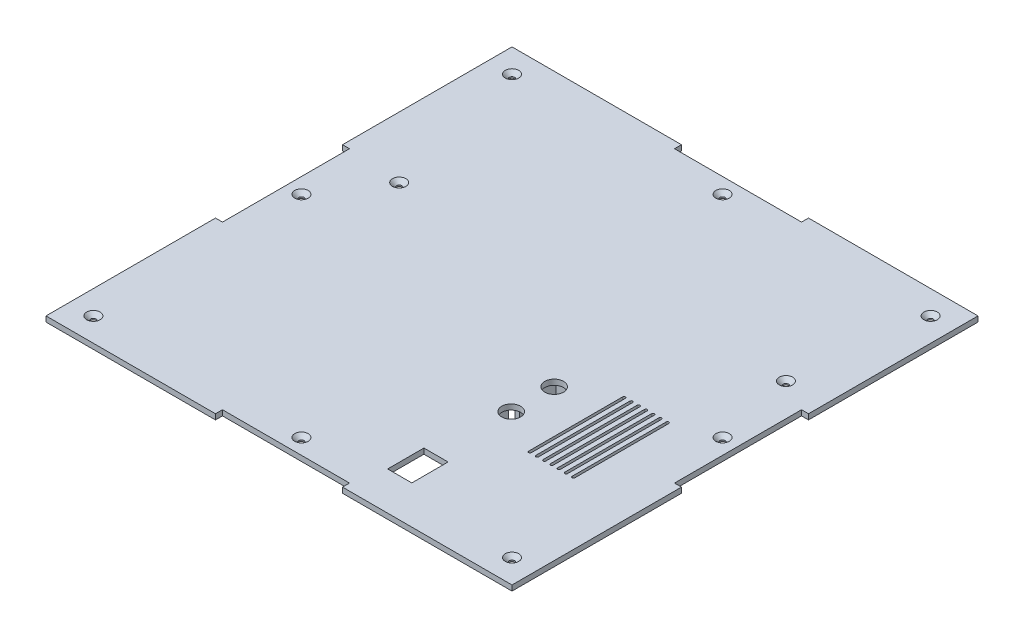
SolidWorks part; units mm, degrees
ref_plane "Front Plane" through (0, 0, 0) normal (0, 0, 1) x (1, 0, 0)
ref_plane "Top Plane" through (0, 0, 0) normal (0, 1, 0) x (1, 0, 0)
ref_plane "Right Plane" through (0, 0, 0) normal (1, 0, 0) x (0, 0, -1)
sketch "Sketch1" plane through (0, 0, 0) normal (0, 1, 0) x (1, 0, 0)
  line L0 (23.4, -87) -> (87, -87) construction
  line L1 (23.4, -84.4) -> (23.4, -87) construction
  line L2 (-23.4, -84.4) -> (23.4, -84.4) construction
  line L3 (-23.4, -87) -> (-23.4, -84.4) construction
  line L4 (-87, -87) -> (-23.4, -87) construction
  line L5 (-87, -23.4) -> (-87, -87) construction
  line L6 (-84.4, -23.4) -> (-87, -23.4) construction
  line L7 (-84.4, 23.4) -> (-84.4, -23.4) construction
  line L8 (-87, 23.4) -> (-84.4, 23.4) construction
  line L9 (-87, 87) -> (-87, 23.4) construction
  line L10 (-23.4, 87) -> (-87, 87) construction
  line L11 (-23.4, 84.4) -> (-23.4, 87) construction
  line L12 (23.4, 84.4) -> (-23.4, 84.4) construction
  line L13 (23.4, 87) -> (23.4, 84.4) construction
  line L14 (87, 87) -> (23.4, 87) construction
  line L15 (87, 23.4) -> (87, 87) construction
  line L16 (84.4, 23.4) -> (87, 23.4) construction
  line L17 (84.4, -23.4) -> (84.4, 23.4) construction
  line L18 (87, -23.4) -> (84.4, -23.4) construction
  line L19 (87, -87) -> (87, -23.4) construction
  line L20 (23.65, -86.75) -> (86.75, -86.75)
  line L21 (86.75, -86.75) -> (86.75, -23.65)
  line L22 (86.75, -23.65) -> (84.15, -23.65)
  line L23 (84.15, -23.65) -> (84.15, 23.65)
  line L24 (84.15, 23.65) -> (86.75, 23.65)
  line L25 (86.75, 23.65) -> (86.75, 86.75)
  line L26 (86.75, 86.75) -> (23.65, 86.75)
  line L27 (23.65, 86.75) -> (23.65, 84.15)
  line L28 (23.65, 84.15) -> (-23.65, 84.15)
  line L29 (-23.65, 84.15) -> (-23.65, 86.75)
  line L30 (-23.65, 86.75) -> (-86.75, 86.75)
  line L31 (-86.75, 86.75) -> (-86.75, 23.65)
  line L32 (-86.75, 23.65) -> (-84.15, 23.65)
  line L33 (-84.15, 23.65) -> (-84.15, -23.65)
  line L34 (-84.15, -23.65) -> (-86.75, -23.65)
  line L35 (-86.75, -23.65) -> (-86.75, -86.75)
  line L36 (-86.75, -86.75) -> (-23.65, -86.75)
  line L37 (-23.65, -86.75) -> (-23.65, -84.15)
  line L38 (-23.65, -84.15) -> (23.65, -84.15)
  line L39 (23.65, -84.15) -> (23.65, -86.75)
  point P20 (0, 84.4)
  point P22 (84.4, 0)
  dimension "D1" = 174
  dimension "D2" = 63.6
  dimension "D3" = 46.8
  dimension "D4" = 174
  dimension "D5" = 63.6
  dimension "D6" = 46.8
  dimension "D7" = 46.8
  dimension "D8" = 63.6
  dimension "D9" = 63.6
  dimension "D10" = 46.8
  dimension "D11" = 2.6
  dimension "D12" = 2.6
  dimension "D13" = 2.6
  dimension "D14" = 2.6
  dimension "D15" = 0.25
extrude "Boss-Extrude1" add sketch "Sketch1" along normal blind 2
sketch "Sketch2" plane through (0, 0, 0) normal (0, -1, 0) x (1, 0, 0)
  circle A0 centre (-77.9289, 77.9289) radius 1
  circle A1 centre (0, 78.4) radius 1
  circle A2 centre (77.9289, 77.9289) radius 1
  circle A3 centre (-78.4, 0) radius 1
  circle A4 centre (78.4, 0) radius 1
  circle A5 centre (72, -30) radius 1
  circle A6 centre (-64, -22) radius 1
  circle A7 centre (-77.9289, -77.9289) radius 1
  circle A8 centre (0, -78.4) radius 1
  circle A9 centre (77.9289, -77.9289) radius 1
  dimension "D1" = 2
  dimension "D2" = 2
  dimension "D3" = 2
  dimension "D4" = 2
  dimension "D5" = 2
  dimension "D6" = 2
  dimension "D7" = 2
  dimension "D8" = 2
  dimension "D9" = 2
  dimension "D10" = 2
extrude "Cut-Extrude1" cut sketch "Sketch2" against normal through all
chamfer "Chamfer1" distance 1.5 angle 45 10 edges at (-77.9289, 2, -78.9289) (0, 2, -79.4) (77.9289, 2, -78.9289) (72, 2, -31) (78.4, 2, -1) (-64, 2, -23) (-78.4, 2, -1) (-77.9289, 2, 76.9289) (0, 2, 77.4) (77.9289, 2, 76.9289)
sketch "Sketch4" plane through (0, 0, 0) normal (0, -1, 0) x (1, 0, 0)
  line L0 (47.2, 40.5) -> (47.2, 5.5) construction
  line L1 (44.2, 40.5) -> (66.2, 40.5) construction
  line L2 (44.2, 40.5) -> (44.2, 5.5) construction
  line L3 (44.2, 5.5) -> (66.2, 5.5) construction
  line L4 (66.2, 40.5) -> (66.2, 5.5) construction
  line L5 (47.7, 40.5) -> (47.7, 5.5)
  line L6 (46.7, 40.5) -> (46.7, 5.5)
  line L7 (44.2, 44) -> (52.2, 44) construction
  line L8 (58.2, 2) -> (66.2, 2) construction
  line L9 (66.2, 44) -> (66.2, 38) construction
  line L10 (44.2, 44) -> (44.2, 38) construction
  line L11 (49.9, 40.5) -> (49.9, 5.5) construction
  line L12 (50.4, 40.5) -> (50.4, 5.5)
  line L13 (49.4, 40.5) -> (49.4, 5.5)
  line L14 (52.6, 40.5) -> (52.6, 5.5) construction
  line L15 (53.1, 40.5) -> (53.1, 5.5)
  line L16 (52.1, 40.5) -> (52.1, 5.5)
  line L17 (55.3, 40.5) -> (55.3, 5.5) construction
  line L18 (55.8, 40.5) -> (55.8, 5.5)
  line L19 (54.8, 40.5) -> (54.8, 5.5)
  line L20 (58, 40.5) -> (58, 5.5) construction
  line L21 (58.5, 40.5) -> (58.5, 5.5)
  line L22 (57.5, 40.5) -> (57.5, 5.5)
  line L23 (60.7, 40.5) -> (60.7, 5.5) construction
  line L24 (61.2, 40.5) -> (61.2, 5.5)
  line L25 (60.2, 40.5) -> (60.2, 5.5)
  line L26 (63.4, 40.5) -> (63.4, 5.5) construction
  line L27 (63.9, 40.5) -> (63.9, 5.5)
  line L28 (62.9, 40.5) -> (62.9, 5.5)
  arc A0 (47.7, 40.5) -> (46.7, 40.5) centre (47.2, 40.5) ccw
  arc A1 (46.7, 5.5) -> (47.7, 5.5) centre (47.2, 5.5) ccw
  arc A2 (50.4, 40.5) -> (49.4, 40.5) centre (49.9, 40.5) ccw
  arc A3 (49.4, 5.5) -> (50.4, 5.5) centre (49.9, 5.5) ccw
  arc A4 (53.1, 40.5) -> (52.1, 40.5) centre (52.6, 40.5) ccw
  arc A5 (52.1, 5.5) -> (53.1, 5.5) centre (52.6, 5.5) ccw
  arc A6 (55.8, 40.5) -> (54.8, 40.5) centre (55.3, 40.5) ccw
  arc A7 (54.8, 5.5) -> (55.8, 5.5) centre (55.3, 5.5) ccw
  arc A8 (58.5, 40.5) -> (57.5, 40.5) centre (58, 40.5) ccw
  arc A9 (57.5, 5.5) -> (58.5, 5.5) centre (58, 5.5) ccw
  arc A10 (61.2, 40.5) -> (60.2, 40.5) centre (60.7, 40.5) ccw
  arc A11 (60.2, 5.5) -> (61.2, 5.5) centre (60.7, 5.5) ccw
  arc A12 (63.9, 40.5) -> (62.9, 40.5) centre (63.4, 40.5) ccw
  arc A13 (62.9, 5.5) -> (63.9, 5.5) centre (63.4, 5.5) ccw
  point P8 (47.2, 23)
  point P25 (49.9, 23)
  point P32 (52.6, 23)
  point P39 (55.3, 23)
  point P46 (58, 23)
  point P53 (60.7, 23)
  point P60 (63.4, 23)
  dimension "D2" = 3
  dimension "D1" = 1
  dimension "D3" = 3.5
  dimension "D4" = 3.5
  dimension "D6" = 4.6
  dimension "D5" = 7
extrude "Cut-Extrude3" cut sketch "Sketch4" against normal through all
sketch "Sketch3" plane through (0, 0, 0) normal (0, -1, 0) x (1, 0, 0)
  line L1 (26.2, 72.5) -> (35.2, 72.5)
  line L2 (26.2, 72.5) -> (26.2, 59)
  line L3 (26.2, 59) -> (35.2, 59)
  line L4 (35.2, 72.5) -> (35.2, 59)
  line L5 (86.75, 86.75) -> (86.75, 23.65) construction
  line L6 (41.95, 59) -> (68.45, 59) construction
  dimension "D1" = 13.5
  dimension "D2" = 9
  dimension "D4" = 51.55
extrude "Cut-Extrude2" cut sketch "Sketch3" against normal through all
sketch "Sketch5" plane through (0, 0, 0) normal (0, -1, 0) x (1, 0, 0)
  line L0 (35.2, 59) -> (35.2, 72.5) construction
  line L1 (23.7, 38.75) -> (37.7, 38.75)
  line L2 (23.7, 38.75) -> (23.7, 7.25)
  line L3 (23.7, 7.25) -> (37.7, 7.25)
  line L4 (37.7, 38.75) -> (37.7, 7.25)
  line L5 (47.7, 5.5) -> (47.7, 40.5) construction
  line L6 (42.7, 0.5) -> (42.7, 45.5) construction
  line L7 (22.2, 40.25) -> (22.2, 5.75)
  line L8 (22.2, 5.75) -> (39.2, 5.75)
  line L9 (39.2, 40.25) -> (39.2, 5.75)
  line L10 (22.2, 40.25) -> (39.2, 40.25)
  point P11 (47.7, 23)
  point P12 (37.7, 23)
  dimension "D1" = 14
  dimension "D2" = 31.5
  dimension "D3" = 5
  dimension "D4" = 1.5
extrude "Boss-Extrude2" add sketch "Sketch5" along normal blind 10 contours L10 L7 L8 L9 L1 L4 L3 L2
sketch "Sketch7" plane through (0, 0, 0) normal (0, -1, 0) x (1, 0, 0)
  line L0 (23.7, 38.75) -> (37.7, 38.75) construction
  line L1 (30.7, 31) -> (30.7, 15) construction
  line L2 (37.7, 38.75) -> (37.7, 7.25) construction
  circle A0 centre (30.7, 15) radius 3.5
  circle A1 centre (30.7, 31) radius 3.5
  point P8 (30.7, 38.75)
  point P9 (37.7, 23)
  point P10 (30.7, 23)
  dimension "D1" = 7
  dimension "D2" = 7
  dimension "D3" = 16
extrude "Cut-Extrude5" cut sketch "Sketch7" against normal through all
sketch "Sketch6" plane through (0, -10, 0) normal (0, -1, 0) x (1, 0, 0)
  line L1 (22.2, 25) -> (23.7, 25)
  line L2 (22.2, 25) -> (22.2, 21)
  line L3 (22.2, 21) -> (23.7, 21)
  line L4 (23.7, 25) -> (23.7, 21)
  line L5 (23.7, 38.75) -> (23.7, 7.25) construction
  line L8 (22.2, 40.25) -> (22.2, 5.75) construction
  point P9 (22.2, 23)
  point P10 (23.7, 23)
  dimension "D1" = 4
extrude "Cut-Extrude4" cut sketch "Sketch6" against normal up to surface (10 mm away) up to face at (30.7, 0, 23)
sketch "Sketch8" plane through (0, 0, 0) normal (0, -1, 0) x (1, 0, 0)
  circle A0 centre (30.7, 31) radius 5
  circle A1 centre (30.7, 15) radius 5
  circle A2 centre (30.7, 31) radius 6
  circle A3 centre (30.7, 15) radius 6
  dimension "D1" = 10
  dimension "D2" = 10
  dimension "D3" = 1
  dimension "D4" = 1
extrude "Boss-Extrude3" add sketch "Sketch8" along normal blind 1
